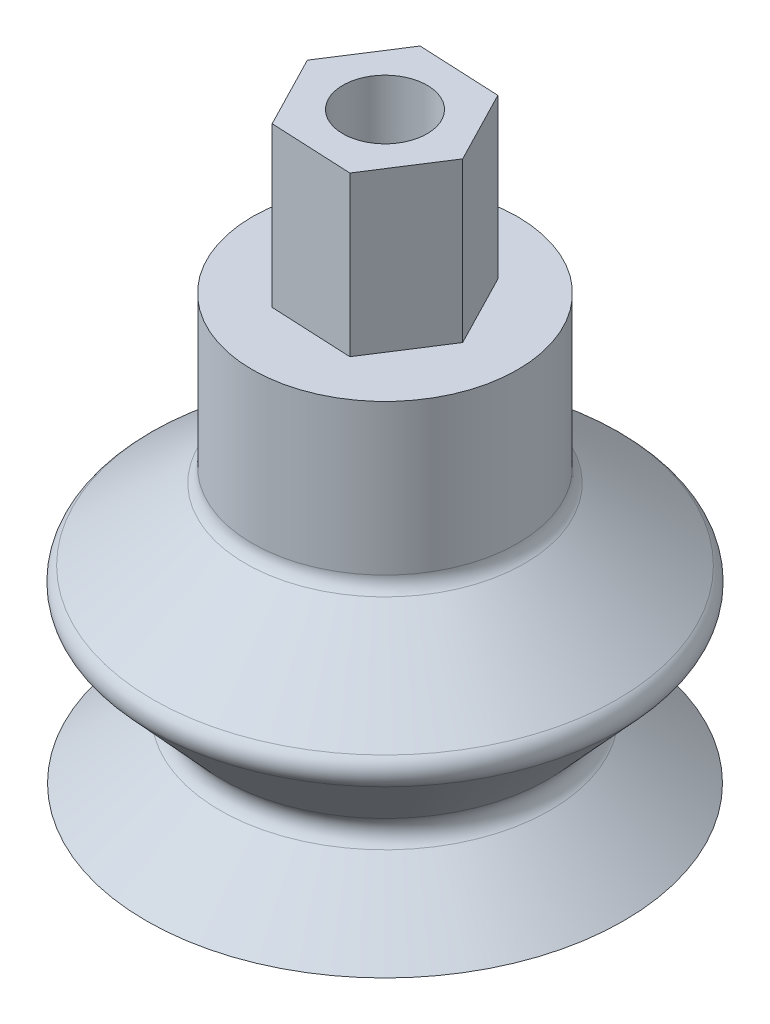
SolidWorks part; units mm, degrees
ref_plane "Front" through (0, 0, 0) normal (0, 0, 1) x (1, 0, 0)
ref_plane "Top" through (0, 0, 0) normal (0, 1, 0) x (1, 0, 0)
ref_plane "Right" through (0, 0, 0) normal (1, 0, 0) x (0, 0, -1)
sketch "Esboço1" plane through (0, 0, 0) normal (0, 0, 1) x (1, 0, 0)
  line L0 (0, 0) -> (13.5, 0)
  line L1 (13.5, 0) -> (8.5, 4)
  line L2 (8.5, 4) -> (14, 10)
  line L3 (14, 10) -> (7.5, 15)
  line L4 (7.5, 15) -> (7.5, 24)
  line L5 (7.5, 24) -> (0, 24)
  line L6 (0, 24) -> (0, 0)
  dimension "D1" = 13.5
  dimension "D2" = 7.5
  dimension "D3" = 14
  dimension "D4" = 8.5
  dimension "D5" = 4
  dimension "D6" = 6
  dimension "D7" = 24
  dimension "D8" = 9
revolve "Revolução1" add sketch "Esboço1" angle 360 about L6
shell "Casca1" thickness 0.9
sketch "Esboço2" plane through (0, 24, 0) normal (0, 1, 0) x (1, 0, 0)
  line L1 (2.4968, 3.8858) -> (-2.1168, 4.1052)
  line L2 (-2.1168, 4.1052) -> (-4.6136, 0.2194)
  line L3 (-4.6136, 0.2194) -> (-2.4968, -3.8858)
  line L4 (-2.4968, -3.8858) -> (2.1168, -4.1052)
  line L5 (2.1168, -4.1052) -> (4.6136, -0.2194)
  line L6 (4.6136, -0.2194) -> (2.4968, 3.8858)
  circle A0 centre (0, 0) radius 4 construction
  dimension "D1" = 8
extrude "Ressalto-extrusão1" add sketch "Esboço2" along normal blind 9
sketch "Esboço3" plane through (0, 33, 0) normal (0, 1, 0) x (1, 0, 0)
  circle A0 centre (0, 0) radius 2.3813
  dimension "D1" = 4.7625
fillet "Filete1" radius 1 3 edges at (-7.5, 15, 0) (-14, 10, 0) (-8.5, 4, 0)
extrude "Corte-extrusão1" cut sketch "Esboço3" against normal through all contours A0
